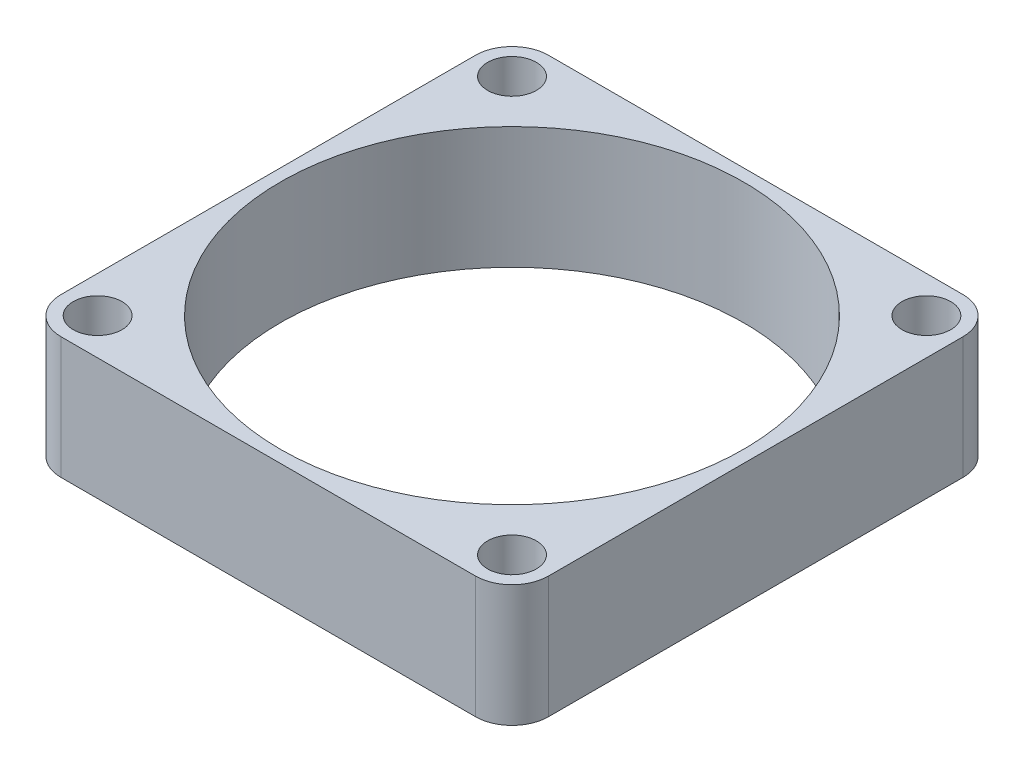
SolidWorks part; units mm, degrees
ref_plane "Front Plane" through (0, 0, 0) normal (0, 0, 1) x (1, 0, 0)
ref_plane "Top Plane" through (0, 0, 0) normal (0, 1, 0) x (1, 0, 0)
ref_plane "Right Plane" through (0, 0, 0) normal (1, 0, 0) x (0, 0, -1)
sketch "Sketch1" plane through (0, 0, 0) normal (0, 1, 0) x (1, 0, 0)
  line L0 (20, 40) -> (20, 0) construction
  line L1 (3, 0) -> (37, 0)
  line L2 (0, 3) -> (0, 37)
  line L3 (3, 40) -> (37, 40)
  line L4 (40, 3) -> (40, 37)
  line L5 (0, 20) -> (40, 20) construction
  arc A0 (37, 40) -> (40, 37) centre (37, 37) cw
  arc A1 (40, 3) -> (37, 0) centre (37, 3) cw
  arc A2 (0, 3) -> (3, 0) centre (3, 3) ccw
  arc A3 (0, 37) -> (3, 40) centre (3, 37) cw
  circle A4 centre (20, 20) radius 19
  circle A5 centre (3, 37) radius 2
  circle A6 centre (37, 37) radius 2
  circle A7 centre (37, 3) radius 2
  circle A8 centre (3, 3) radius 2
  point P11 (0, 0)
  dimension "D1" = 3
  dimension "D4" = 20
  dimension "D6" = 38
  dimension "D7" = 4
  dimension "D8" = 3
  dimension "D2" = 34
  dimension "D3" = 34
  dimension "D5" = 20
extrude "Boss-Extrude1" add sketch "Sketch1" along normal blind 10
